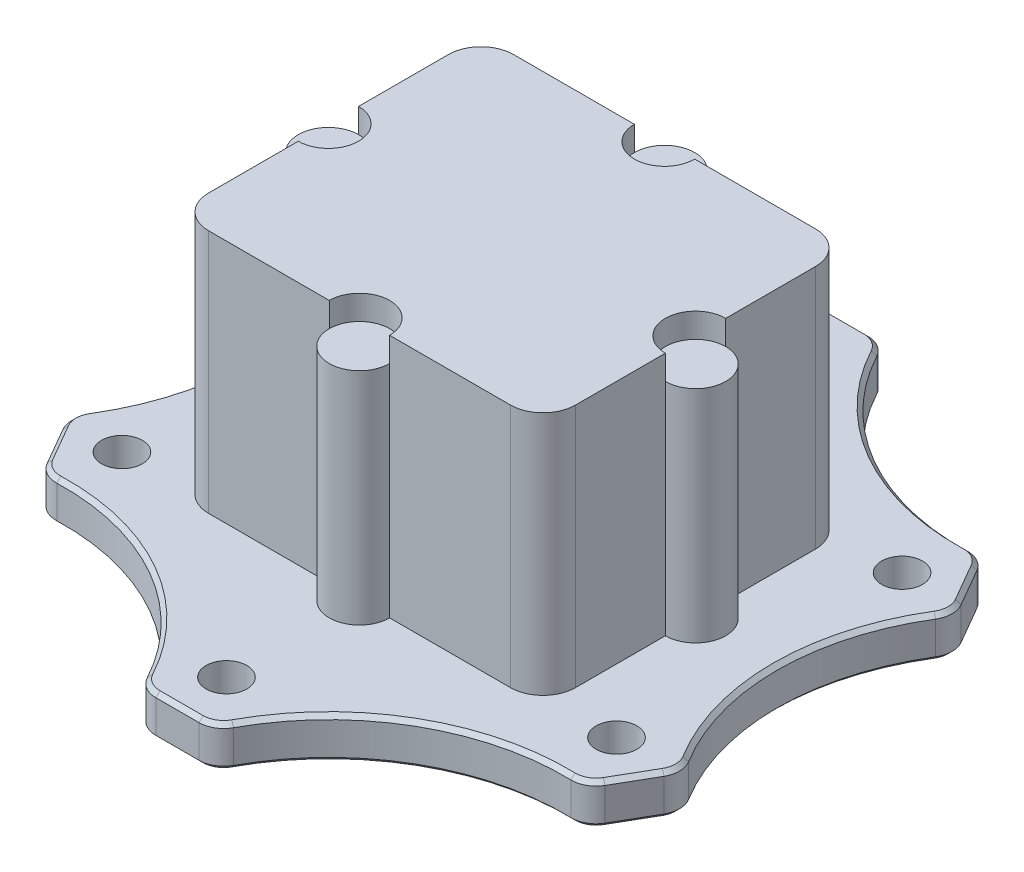
SolidWorks part; units mm, degrees
ref_plane "Front Plane" through (0, 0, 0) normal (0, 0, 1) x (1, 0, 0)
ref_plane "Top Plane" through (0, 0, 0) normal (0, 1, 0) x (1, 0, 0)
ref_plane "Right Plane" through (0, 0, 0) normal (1, 0, 0) x (0, 0, -1)
ref_plane "Plane1" through (0, 227, 0) normal (0, -1, 0) x (1, 0, 0)
sketch "Sketch1" plane through (0, 227, 0) normal (0, -1, 0) x (1, 0, 0)
  line L0 (610.4723, 48.998) -> (619.4723, 48.998)
  line L1 (648.2294, 65.6009) -> (652.7294, 73.3951)
  line L2 (652.7294, 106.6009) -> (648.2294, 114.3951)
  line L3 (619.4723, 130.998) -> (610.4723, 130.998)
  line L4 (581.7153, 114.3951) -> (577.2153, 106.6009)
  line L5 (577.2153, 73.3951) -> (581.7153, 65.6009)
  arc A0 (581.7153, 65.6009) -> (610.4723, 48.998) centre (584.2992, 36.8706) cw
  arc A1 (619.4723, 48.998) -> (648.2294, 65.6009) centre (645.6455, 36.8706) cw
  arc A2 (652.7294, 73.3951) -> (652.7294, 106.6009) centre (676.3186, 89.998) cw
  arc A3 (648.2294, 114.3951) -> (619.4723, 130.998) centre (645.6455, 143.1255) cw
  arc A4 (610.4723, 130.998) -> (581.7153, 114.3951) centre (584.2992, 143.1255) cw
  arc A5 (577.2153, 106.6009) -> (577.2153, 73.3951) centre (553.626, 89.998) cw
extrude "Boss-Extrude1" add sketch "Sketch1" against normal blind 5
hole_wizard "#10 Clearance Hole1" positions "Sketch3" profile "Sketch2" hole size "#10" standard "ANSI Inch"
sketch "Sketch3" plane through (0, 232, 0) normal (0, 1, 0) x (1, 0, 0)
  point P0 (614.9723, -124.998)
  point P1 (584.6614, -72.498)
  point P2 (584.6614, -107.498)
  point P3 (614.9723, -54.998)
  point P4 (645.2832, -107.498)
  point P5 (645.2832, -72.498)
sketch "Sketch2" plane through (614.9723, 232, 124.998) normal (1, 0, 0) x (0, 0, 1)
  line L0 (0, 0) -> (0, 5)
  line L1 (0, 5) -> (2.5, 5)
  line L2 (2.5, 5) -> (2.5, 0)
  line L5 (2.5, 0) -> (0, 0)
  line L11 (0, -6.35) -> (0, 107.95) construction
  dimension "Thru Hole Dia." = 5
  dimension "Thru Hole Depth" = 5
fillet "Fillet1" radius 3 12 edges at (652.7294, 229.5, 106.6009) (577.2153, 229.5, 106.6009) (581.7153, 229.5, 65.6009) (648.2294, 229.5, 65.6009) (652.7294, 229.5, 73.3951) (619.4723, 229.5, 130.998) (648.2294, 229.5, 114.3951) (619.4723, 229.5, 48.998) (577.2153, 229.5, 73.3951) (610.4723, 229.5, 48.998) (610.4723, 229.5, 130.998) (581.7153, 229.5, 114.3951)
chamfer "Chamfer1" distance 0.5 angle 45 48 edges at (648.0194, 232, 66.0846) (650.4794, 232, 69.498) (631.2223, 232, 61.8522) (652.2055, 232, 73.3351) (619.1585, 232, 49.4217) (647.4723, 232, 89.998) (614.9723, 232, 48.998) (652.2055, 232, 106.6609) (610.7862, 232, 49.4217) (650.4794, 232, 110.498) (598.7223, 232, 61.8522) (648.0194, 232, 113.9115) (581.9252, 232, 66.0846) (631.2223, 232, 118.1438) (579.4653, 232, 69.498) (619.1585, 232, 130.5744) (577.7391, 232, 73.3351) (614.9723, 232, 130.998) (582.4723, 232, 89.998) (610.7862, 232, 130.5744) (577.7391, 232, 106.6609) (598.7223, 232, 118.1438) (579.4653, 232, 110.498) (581.9252, 232, 113.9115) (631.2223, 227, 118.1438) (619.1585, 227, 130.5744) (648.0194, 227, 113.9115) (614.9723, 227, 130.998) (650.4794, 227, 110.498) (610.7862, 227, 130.5744) (652.2055, 227, 106.6609) (598.7223, 227, 118.1438) (647.4723, 227, 89.998) (581.9252, 227, 113.9115) (652.2055, 227, 73.3351) (579.4653, 227, 110.498) (650.4794, 227, 69.498) (577.7391, 227, 106.6609) (648.0194, 227, 66.0846) (582.4723, 227, 89.998) (631.2223, 227, 61.8522) (577.7391, 227, 73.3351) (619.1585, 227, 49.4217) (579.4653, 227, 69.498) (614.9723, 227, 48.998) (581.9252, 227, 66.0846) (610.7862, 227, 49.4217) (598.7223, 227, 61.8522)
sketch "Sketch4" plane through (0, 232, 0) normal (0, 1, 0) x (1, 0, 0)
  line L0 (614.9723, -54.998) -> (614.9723, -124.998) construction
  line L1 (584.6614, -107.498) -> (645.2832, -72.498) construction
  line L3 (596.4723, -108.698) -> (633.4723, -108.698)
  line L4 (592.4723, -104.698) -> (592.4723, -75.298)
  line L5 (596.4723, -71.298) -> (633.4723, -71.298)
  line L6 (637.4723, -104.698) -> (637.4723, -75.298)
  line L7 (592.4723, -108.698) -> (637.4723, -71.298) construction
  line L8 (592.4723, -71.298) -> (637.4723, -108.698) construction
  arc A0 (596.4723, -108.698) -> (592.4723, -104.698) centre (596.4723, -104.698) cw
  arc A1 (633.4723, -108.698) -> (637.4723, -104.698) centre (633.4723, -104.698) ccw
  arc A2 (633.4723, -71.298) -> (637.4723, -75.298) centre (633.4723, -75.298) cw
  arc A3 (592.4723, -75.298) -> (596.4723, -71.298) centre (596.4723, -75.298) cw
  circle A4 centre (614.9723, -71.298) radius 3.7
  circle A5 centre (592.4723, -89.998) radius 3.7
  circle A6 centre (614.9723, -108.698) radius 3.7
  circle A7 centre (637.4723, -89.998) radius 3.7
  point P8 (614.9723, -89.998)
  dimension "D3" = 4
  dimension "D4" = 7.4
  dimension "D1" = 45
  dimension "D2" = 37.4
extrude "Boss-Extrude4" add sketch "Sketch4" along normal blind 30 contours A7 L6 A2 L5 A4 A3 L4 A5 A0 L3 A6 A1
sketch "Sketch5" plane through (0, 232, 0) normal (0, 1, 0) x (1, 0, 0)
  line L0 (637.4723, -104.698) -> (637.4723, -75.298) construction
  line L1 (596.4723, -108.698) -> (633.4723, -108.698) construction
  circle A4 centre (614.9723, -71.298) radius 3.7
  circle A5 centre (637.4723, -89.998) radius 3.7
  circle A6 centre (614.9723, -108.698) radius 3.7
  circle A7 centre (592.4723, -89.998) radius 3.7
extrude "Boss-Extrude5" add sketch "Sketch5" along normal blind 27 contours A7 | A4 | A5 | A6
